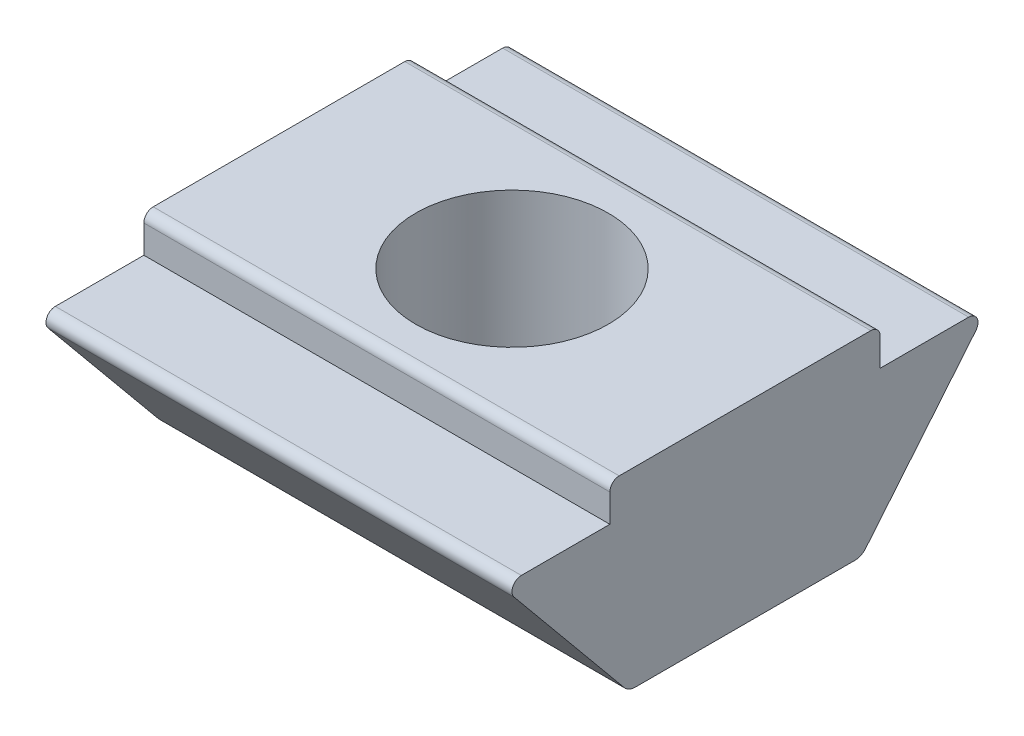
SolidWorks part; units mm, degrees
ref_plane "Front Plane" through (0, 0, 0) normal (0, 0, 1) x (1, 0, 0)
ref_plane "Top Plane" through (0, 0, 0) normal (0, 1, 0) x (1, 0, 0)
ref_plane "Right Plane" through (0, 0, 0) normal (1, 0, 0) x (0, 0, -1)
sketch "Sketch1" plane through (0, 0, 0) normal (1, 0, 0) x (0, 0, -1)
  line L0 (2.5, -3.3) -> (-2.5, -3.3)
  line L1 (-2.5, -3.3) -> (-4.9542, -0.3273)
  line L2 (-4.8, 0) -> (-2.9, 0)
  line L3 (-2.9, 0) -> (-2.9, 0.8)
  line L4 (-2.9, 0.8) -> (2.9, 0.8)
  line L5 (2.9, 0.8) -> (2.9, 0)
  line L6 (2.9, 0) -> (4.8, 0)
  line L7 (4.9542, -0.3273) -> (2.5, -3.3)
  line L8 (0, 0.8) -> (0, -3.3) construction
  line L9 (5, -0.2) -> (5, 0) construction
  line L10 (-5, 0) -> (-5, -0.2) construction
  line L11 (-4.8, 0) -> (-5, 0) construction
  line L12 (4.8, 0) -> (5, 0) construction
  arc A0 (-4.9542, -0.3273) -> (-4.8, 0) centre (-4.8, -0.2) cw
  arc A1 (4.8, 0) -> (4.9542, -0.3273) centre (4.8, -0.2) cw
  point P13 (-5.2245, 0)
  point P16 (5.2245, 0)
  dimension "FIX_4" = 0.2
  dimension "FIX_2" = 5.8
  dimension "E" = 3.3
  dimension "T" = 4.1
  dimension "FIX_1" = 10
  dimension "FIX_3" = 5
extrude "Boss-Extrude1" add sketch "Sketch1" along normal mid plane 10
fillet "Fillet1" radius 0.3 2 edges at (0, -3.3, 2.5) (0, -3.3, -2.5)
fillet "Fillet2" radius 0.2 2 edges at (0, 0.8, -2.9) (0, 0.8, 2.9)
hole_wizard "Tapped Hole1" positions "Sketch3" profile "Sketch2" tap size "M5x0.8" standard "JIS" end condition through all
sketch "Sketch3" plane through (0, 0.8, 0) normal (0, 1, 0) x (1, 0, 0)
  point P0 (0, 0)
sketch "Sketch2" plane through (0, 0.8, 0) normal (1, 0, 0) x (0, 0, 1)
  line L0 (0, 0) -> (0, 4.1)
  line L1 (0, 4.1) -> (2.067, 4.1)
  line L2 (2.067, 4.1) -> (2.067, 0)
  line L5 (2.067, 0) -> (0, 0)
  line L11 (0, -6.35) -> (0, 107.95) construction
  dimension "Thru Tap Drill Dia." = 4.134
  dimension "Thru Tap Drill Depth" = 4.1
cosmetic thread "Thread1" parameters "M"=5
ref_plane "Plane1" [suppressed] through (0, 0, -4.1) normal (0, 0, 1) x (1, 0, 0)
sketch "Sketch4" [suppressed] plane through (0, 0, -4.1) normal (0, 0, 1) x (1, 0, 0)
  line L0 (0, 0.1) -> (0, -0.1) construction
  line L1 (-3, 0.1) -> (-3, -0.1)
  line L2 (-3, 0.1) -> (-3, -0.1) construction
  arc A0 (-3, 0.1) -> (-3, -0.1) centre (-3, 0) ccw
  dimension "FIX_10" = 0.1
  dimension "FIX_9" = 6
revolve "Revolve1" [suppressed] add sketch "Sketch4" angle 360 about L2
pattern_linear "LPattern1" [suppressed]
